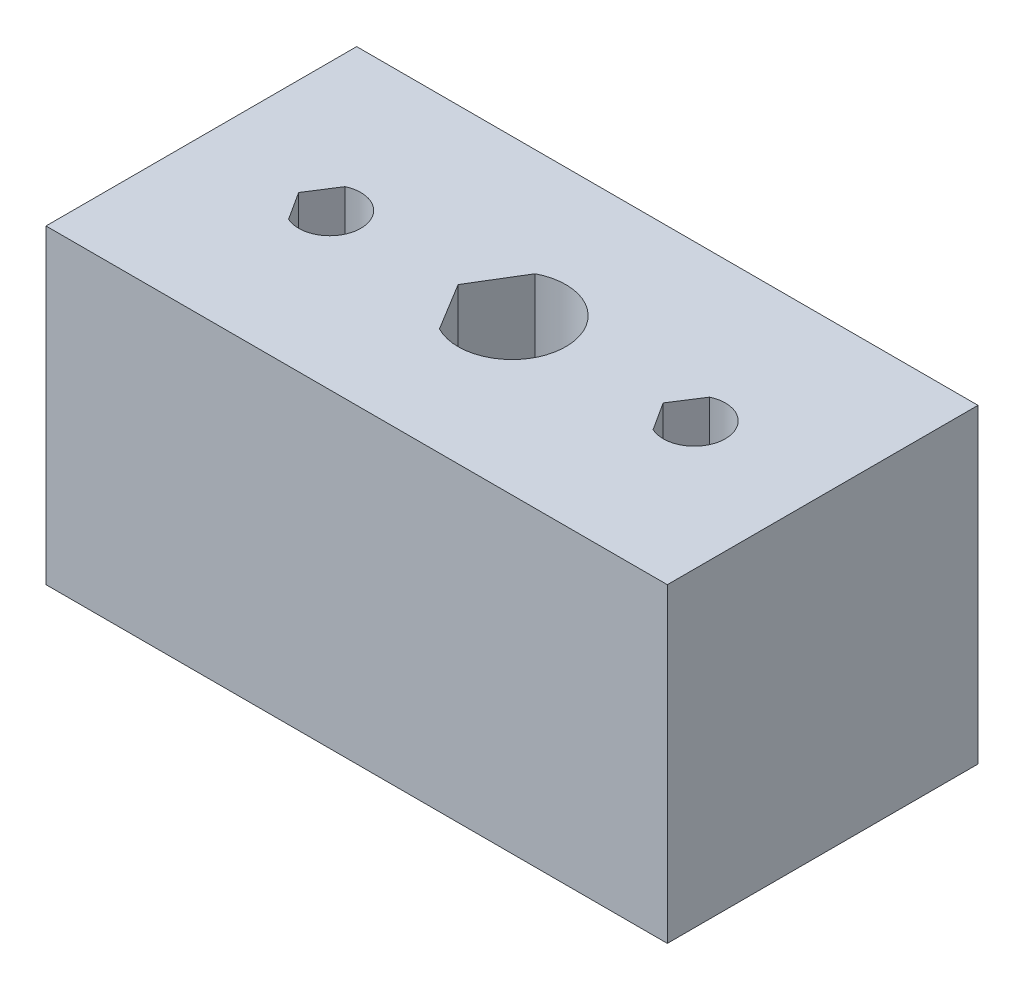
SolidWorks part; units mm, degrees
ref_plane "Front Plane" through (0, 0, 0) normal (0, 0, 1) x (1, 0, 0)
ref_plane "Top Plane" through (0, 0, 0) normal (0, 1, 0) x (1, 0, 0)
ref_plane "Right Plane" through (0, 0, 0) normal (1, 0, 0) x (0, 0, -1)
sketch "Sketch1" plane through (0, 0, 0) normal (0, 1, 0) x (1, 0, 0)
  line L1 (-15, -7.5) -> (15, -7.5)
  line L2 (-15, -7.5) -> (-15, 7.5)
  line L3 (-15, 7.5) -> (15, 7.5)
  line L4 (15, -7.5) -> (15, 7.5)
  line L5 (-15, -7.5) -> (15, 7.5) construction
  line L6 (-15, 7.5) -> (15, -7.5) construction
  point P0 (0, 0)
  dimension "D1" = 15
  dimension "D2" = 30
extrude "Boss-Extrude1" add sketch "Sketch1" along normal blind 15
sketch "Sketch2" plane through (0, 15, 0) normal (0, 1, 0) x (1, 0, 0)
  line L1 (-15, 7.5) -> (-15, -7.5) construction
  line L2 (15, -7.5) -> (15, 7.5) construction
  line L3 (-10.3, 0) -> (-9.4248, -1.3637)
  line L4 (-10.3, 0) -> (-9.4248, 1.3637)
  line L5 (-2.6, 0) -> (-1.1951, -2.3091)
  line L6 (-2.6, 0) -> (-1.1951, 2.3091)
  line L7 (7.3, 0) -> (8.1752, -1.3637)
  line L8 (7.3, 0) -> (8.1752, 1.3637)
  arc A0 (-1.1951, -2.3091) -> (-1.1951, 2.3091) centre (0, 0) ccw
  arc A1 (-9.4248, -1.3637) -> (-9.4248, 1.3637) centre (-8.8, 0) ccw
  arc A2 (8.1752, -1.3637) -> (8.1752, 1.3637) centre (8.8, 0) ccw
  dimension "D1" = 5.2
  dimension "D2" = 3
  dimension "D3" = 3
  dimension "D4" = 6.2
  dimension "D5" = 6.2
extrude "Cut-Extrude1" cut sketch "Sketch2" against normal through all
